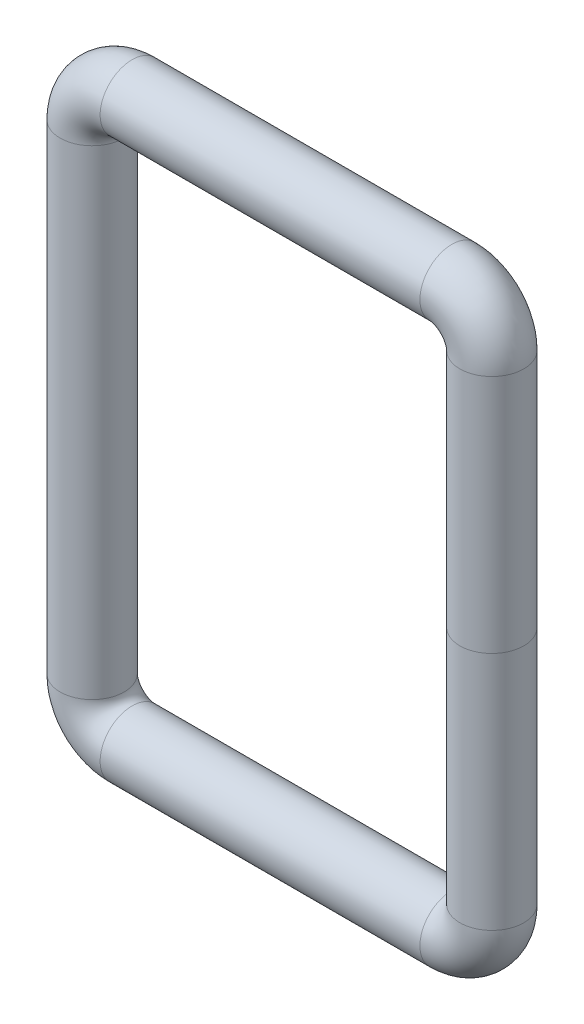
SolidWorks part; units mm, degrees
material "Copper"
ref_plane "Front Plane" through (0, 0, 0) normal (0, 0, 1) x (1, 0, 0)
ref_plane "Top Plane" through (0, 0, 0) normal (0, 1, 0) x (1, 0, 0)
ref_plane "Right Plane" through (0, 0, 0) normal (1, 0, 0) x (0, 0, -1)
sketch "Sketch1" plane through (0, 0, 0) normal (0, 0, 1) x (1, 0, 0)
  line L0 (-2, 3) -> (-2, -3) construction
  line L1 (-2, -3) -> (2, -3) construction
  line L2 (2, -3) -> (2, 3) construction
  line L3 (2, 3) -> (-2, 3) construction
  line L4 (-2.5, 3) -> (-2.5, -3)
  line L5 (-2, -3.5) -> (2, -3.5)
  line L6 (2.5, -3) -> (2.5, 3)
  line L7 (2, 3.5) -> (-2, 3.5)
  line L8 (2.5, -3.5) -> (2.5, 3.5) construction
  line L9 (-2.5, -3.5) -> (2.5, -3.5) construction
  line L10 (2.5, 3.5) -> (-2.5, 3.5) construction
  line L11 (-2.5, 3.5) -> (-2.5, -3.5) construction
  arc A0 (2.5, -3) -> (2, -3.5) centre (2, -3) cw
  arc A1 (2.5, 3) -> (2, 3.5) centre (2, 3) ccw
  arc A2 (-2.5, -3) -> (-2, -3.5) centre (-2, -3) ccw
  arc A3 (-2.5, 3) -> (-2, 3.5) centre (-2, 3) cw
  point P2 (-2, 0)
  point P5 (2, 0)
  point P7 (0, 3)
  dimension "D4" = 0.5
  dimension "D1" = 6
  dimension "D2" = 4
  dimension "D3" = 0.5
sketch "Sketch2" plane through (0, 0, 0) normal (0, 1, 0) x (1, 0, 0)
  line L0 (2, 0) -> (2.5, 0) construction
  line L1 (2, 0) -> (2.5, 0) construction
  circle A0 centre (2.5, 0) radius 0.4
  dimension "D1" = 0.8
sweep "Sweep1" add profiles "Sketch2" path "Sketch1"
